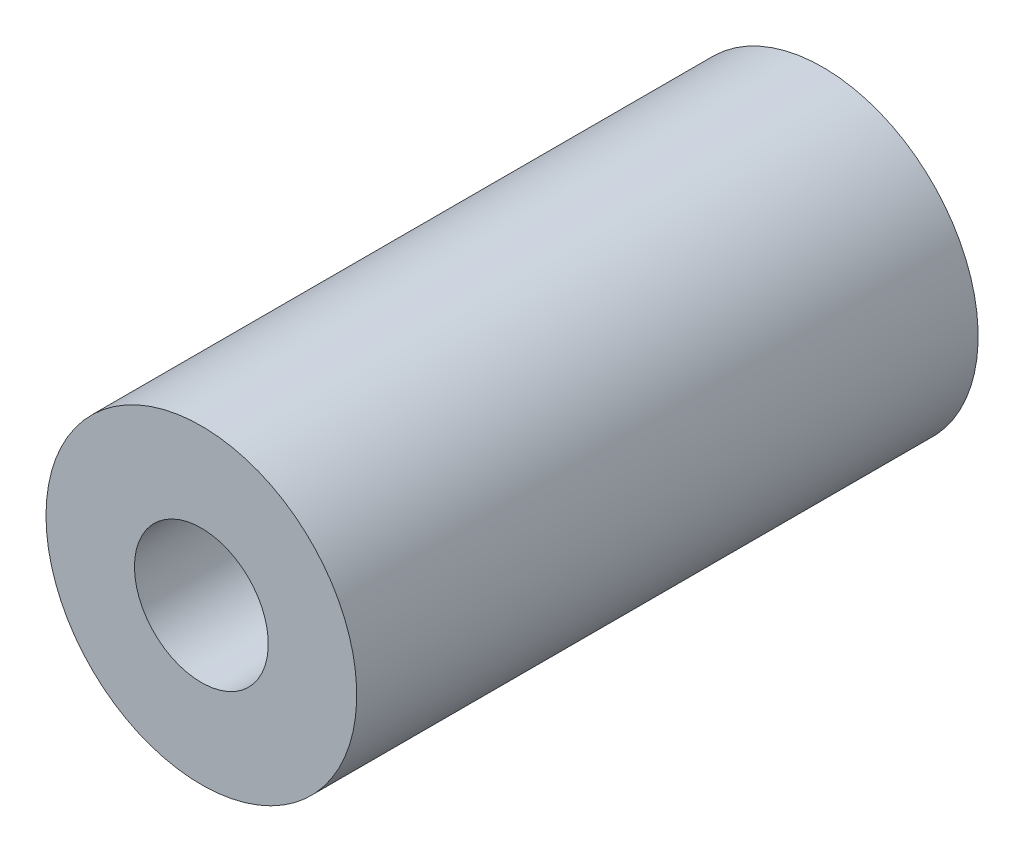
SolidWorks part; units mm, degrees
material "6061 Alloy"
ref_plane "Front Plane" through (0, 0, 0) normal (0, 0, 1) x (1, 0, 0)
ref_plane "Top Plane" through (0, 0, 0) normal (0, 1, 0) x (1, 0, 0)
ref_plane "Right Plane" through (0, 0, 0) normal (1, 0, 0) x (0, 0, -1)
sketch "Sketch1" plane through (0, 0, 0) normal (0, 0, 1) x (1, 0, 0)
  circle A0 centre (0, 0) radius 9.525
  circle A1 centre (0, 0) radius 4.1021
  dimension "D1" = 19.05
  dimension "D2" = 8.2042
extrude "Boss-Extrude1" add sketch "Sketch1" along normal mid plane 38.1
